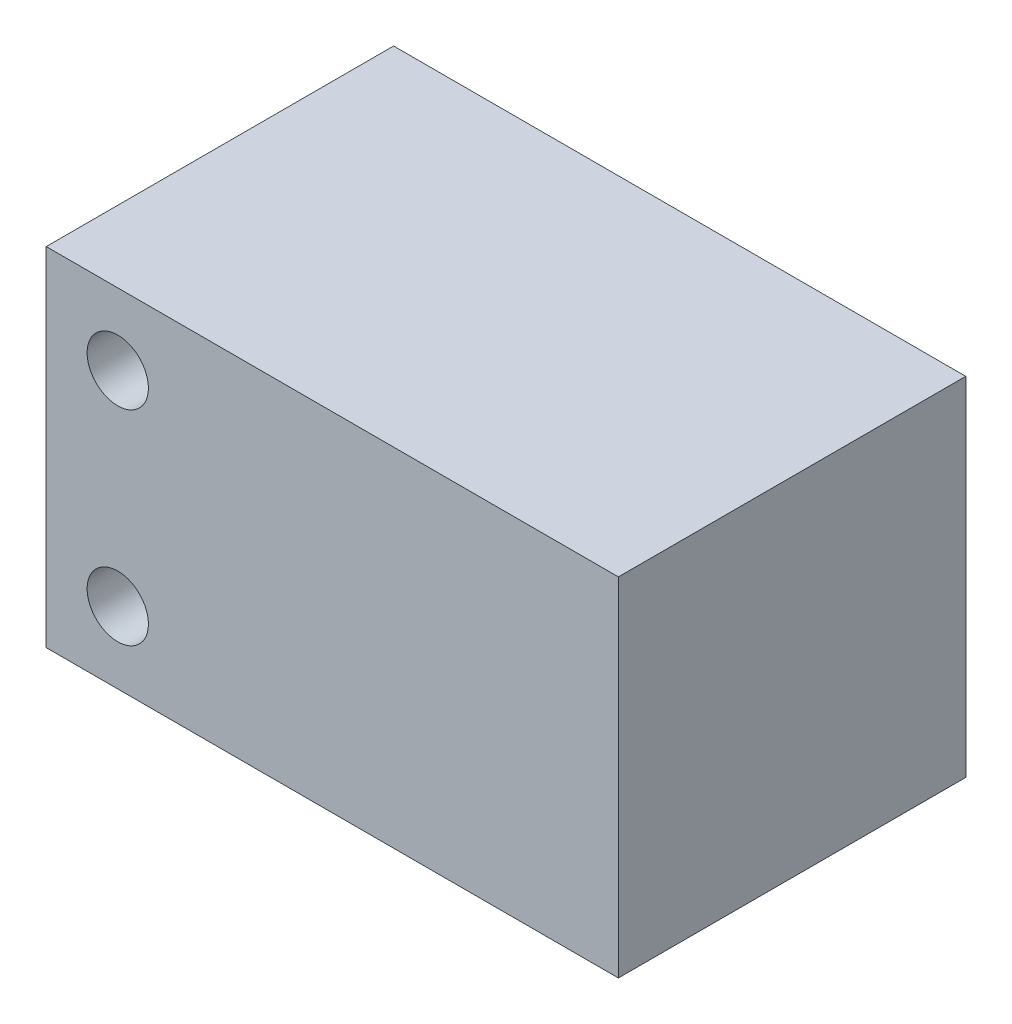
SolidWorks part; units mm, degrees
ref_plane "前视基准面" through (0, 0, 0) normal (0, 0, 1) x (1, 0, 0)
ref_plane "上视基准面" through (0, 0, 0) normal (0, 1, 0) x (1, 0, 0)
ref_plane "右视基准面" through (0, 0, 0) normal (1, 0, 0) x (0, 0, -1)
sketch "草图1" plane through (0, 0, 0) normal (0, 0, 1) x (1, 0, 0)
  line L1 (0, 0) -> (28, 0)
  line L2 (0, 0) -> (0, 17)
  line L3 (0, 17) -> (28, 17)
  line L4 (28, 0) -> (28, 17)
  dimension "D1" = 28
  dimension "D2" = 17
extrude "凸台-拉伸1" add sketch "草图1" along normal blind 17
sketch "草图2" plane through (0, 0, 17) normal (0, 0, 1) x (1, 0, 0)
  line L0 (28, 17) -> (0, 17) construction
  line L2 (0, 17) -> (0, 0) construction
  circle A0 centre (3.5, 13.5) radius 1.5
  circle A1 centre (3.5, 3.5) radius 1.5
  dimension "D1" = 3
  dimension "D2" = 3
  dimension "D3" = 10
  dimension "D4" = 3.5
  dimension "D5" = 3.5
  dimension "D6" = 3.5
extrude "切除-拉伸1" cut sketch "草图2" against normal through all
